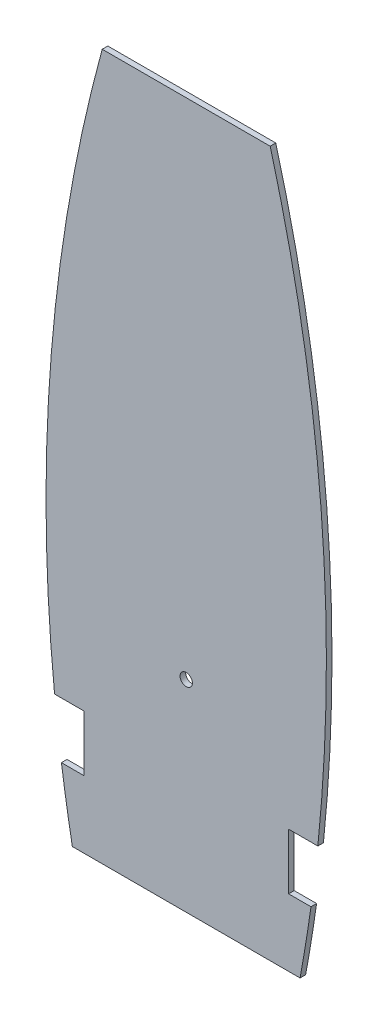
SolidWorks part; units mm, degrees
material "A-Glass Fiber"
ref_plane "Plan de face" through (0, 0, 0) normal (0, 0, 1) x (1, 0, 0)
ref_plane "Plan de dessus" through (0, 0, 0) normal (0, 1, 0) x (1, 0, 0)
ref_plane "Plan de droite" through (0, 0, 0) normal (1, 0, 0) x (0, 0, -1)
sketch "Sketch2" plane through (0, 0, 0) normal (0, 0, 1) x (1, 0, 0)
  line L0 (0, 0) -> (0, -350) construction
  line L1 (-75, 0) -> (75, 0)
  line L2 (125, -350) -> (-125, -350) construction
  line L3 (72.4663, -755.6809) -> (4.8134, -996.3531)
  line L5 (-72.4663, -755.6809) -> (-4.8134, -996.3531)
  arc A0 (75, 0) -> (72.4663, -755.6809) centre (-1287.9254, -373.2751) cw
  arc A1 (4.8134, -996.3531) -> (0, -1000) centre (0, -995) cw
  arc A2 (-75, 0) -> (-72.4663, -755.6809) centre (1287.9254, -373.2751) ccw
  arc A3 (0, -1000) -> (-4.8134, -996.3531) centre (0, -995) cw
  point P8 (0, -350)
  dimension "D3" = 5
  dimension "D1" = 350
  dimension "D2" = 250
  dimension "D4" = 250
extrude "Boss-Extrude1" add sketch "Sketch2" along normal blind 5
sketch "Sketch3" plane through (0, 0, 0) normal (0, 0, -1) x (-1, 0, 0)
  circle A0 centre (0, -450) radius 5.5
  point P2 (0, 0)
  dimension "D2" = 11
  dimension "D1" = 450
extrude "Cut-Extrude1" cut sketch "Sketch3" against normal through all
sketch "Sketch4" plane through (0, 0, 0) normal (0, 0, -1) x (-1, 0, 0)
  line L0 (-117.5538, -520) -> (-91.4313, -520)
  line L1 (-91.4313, -520) -> (-91.4313, -570)
  line L2 (-91.4313, -570) -> (-111.4313, -570)
  line L3 (-75, 0) -> (75, 0) construction
  line L4 (0, 2.75) -> (0, -2.75) construction
  line L5 (117.5538, -520) -> (91.4313, -520)
  line L6 (91.4313, -520) -> (91.4313, -570)
  line L7 (91.4313, -570) -> (111.4313, -570)
  line L8 (101.6761, -630) -> (-101.6761, -630)
  line L9 (-101.6761, -630) -> (-101.6761, -1039.9584)
  line L10 (-101.6761, -1039.9584) -> (101.6761, -1039.9584)
  line L11 (101.6761, -1039.9584) -> (101.6761, -630)
  arc A0 (-75, 0) -> (-72.4663, -755.6809) centre (1287.9254, -373.2751) ccw construction
  arc A1 (-117.5538, -520) -> (-111.4313, -570) centre (-91.4313, -542.1762) ccw
  arc A2 (117.5538, -520) -> (111.4313, -570) centre (91.4313, -542.1762) cw
  arc A3 (72.4663, -755.6809) -> (75, 0) centre (-1287.9254, -373.2751) ccw construction
  dimension "D1" = 520
  dimension "D2" = 50
  dimension "D3" = 20
  dimension "D4" = 630
extrude "Cut-Extrude2" cut sketch "Sketch4" against normal through all
